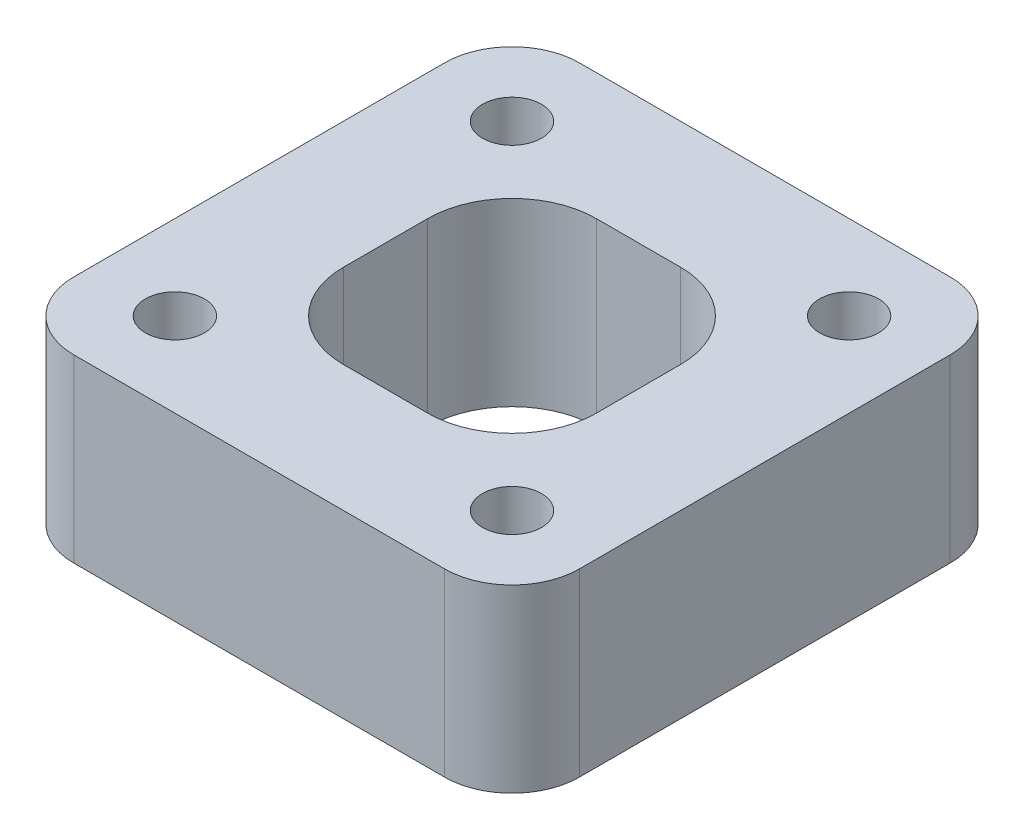
SolidWorks part; units mm, degrees
ref_plane "Спереди" through (0, 0, 0) normal (0, 0, 1) x (1, 0, 0)
ref_plane "Сверху" through (0, 0, 0) normal (0, 1, 0) x (1, 0, 0)
ref_plane "Справа" through (0, 0, 0) normal (1, 0, 0) x (0, 0, -1)
sketch "Эскиз1" plane through (0, 0, 0) normal (0, 1, 0) x (1, 0, 0)
  line L1 (-15, -15) -> (15, -15)
  line L2 (-15, -15) -> (-15, 15)
  line L3 (-15, 15) -> (15, 15)
  line L4 (15, -15) -> (15, 15)
  line L5 (-15, -15) -> (15, 15) construction
  line L6 (-15, 15) -> (15, -15) construction
  point P0 (0, 0)
  dimension "D2" = 30
extrude "тело" add sketch "Эскиз1" along normal mid plane 10.7
sketch "Эскиз2" plane through (0, -5.35, 0) normal (0, 1, 0) x (1, 0, 0)
  line L1 (-10, -10) -> (10, -10) construction
  line L2 (-10, -10) -> (-10, 10) construction
  line L3 (-10, 10) -> (10, 10) construction
  line L4 (10, -10) -> (10, 10) construction
  line L5 (-10, -10) -> (10, 10) construction
  line L6 (-10, 10) -> (10, -10) construction
  circle A0 centre (-10, 10) radius 1.75
  circle A1 centre (10, 10) radius 1.75
  circle A2 centre (10, -10) radius 1.75
  circle A3 centre (-10, -10) radius 1.75
  point P0 (0, 0)
  dimension "D1" = 3.5
  dimension "D3" = 20
extrude "крежные отверстия колеса" cut sketch "Эскиз2" along normal through all
sketch "Эскиз4" plane through (0, 5.35, 0) normal (0, 1, 0) x (1, 0, 0)
  line L1 (-7.5, 7.5) -> (7.5, 7.5)
  line L2 (-7.5, 7.5) -> (-7.5, -7.5)
  line L3 (-7.5, -7.5) -> (7.5, -7.5)
  line L4 (7.5, 7.5) -> (7.5, -7.5)
  point P4 (7.5, 0)
  point P5 (0, 7.5)
  dimension "D1" = 15
extrude "По центру для облегчения" cut sketch "Эскиз4" against normal through all
fillet "Скругление3" radius 5 4 edges at (-7.5, 0, 7.5) (7.5, 0, 7.5) (7.5, 0, -7.5) (-7.5, 0, -7.5)
fillet "Скругление6" radius 4 4 edges at (-15, 0, 15) (-15, 0, -15) (15, 0, -15) (15, 0, 15)
